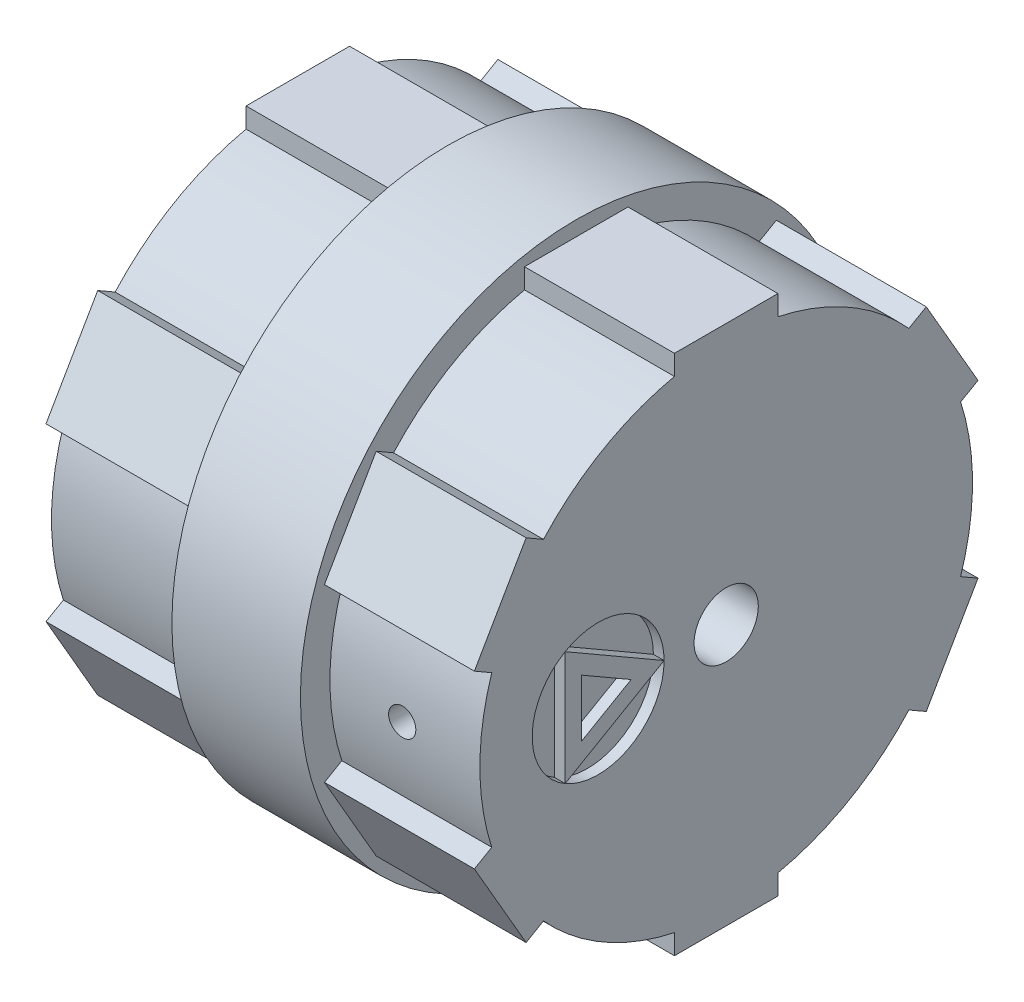
SolidWorks part; units mm, degrees
ref_plane "Front" through (0, 0, 0) normal (0, 0, 1) x (1, 0, 0)
ref_plane "Top" through (0, 0, 0) normal (0, 1, 0) x (1, 0, 0)
ref_plane "Right" through (0, 0, 0) normal (1, 0, 0) x (0, 0, -1)
sketch "Croquis1" plane through (0, 0, 0) normal (1, 0, 0) x (0, 0, -1)
  circle A0 centre (0, 0) radius 11.5
  dimension "D1" = 23
extrude "Saliente-Extruir1" add sketch "Croquis1" along normal blind 20
shell "Vaciado2" thickness 3
sketch "Croquis2" plane through (20, 0, 0) normal (1, 0, 0) x (0, 0, -1)
  circle A0 centre (0, 0) radius 1.5
extrude "Cortar-Extruir1" cut sketch "Croquis2" against normal blind 20
sketch "Croquis3" plane through (20, 0, 0) normal (1, 0, 0) x (0, 0, -1)
  line L0 (0, 13.2158) -> (0, -18.6677) construction
  line L1 (8.1622, 7.5015) -> (11.7564, 3.9985) construction
  line L2 (-2.4154, 10.8194) -> (2.4154, 10.8194)
  line L3 (-2.4154, 10.8194) -> (-2.4154, 12.1806)
  line L4 (-2.4154, 12.1806) -> (2.4154, 12.1806)
  line L5 (2.4154, 10.8194) -> (2.4154, 12.1806)
  line L6 (-2.4154, 10.8194) -> (2.4154, 12.1806) construction
  line L7 (-2.4154, 12.1806) -> (2.4154, 10.8194) construction
  line L8 (9.341, 8.1821) -> (10.5776, 3.3179) construction
  line L9 (8.1622, 7.5015) -> (9.341, 8.1821)
  line L10 (8.1622, 7.5015) -> (10.5776, 3.3179)
  line L11 (10.5776, 3.3179) -> (11.7564, 3.9985)
  line L12 (9.341, 8.1821) -> (11.7564, 3.9985)
  line L13 (10.5776, -3.3179) -> (9.341, -8.1821) construction
  line L14 (11.7564, -3.9985) -> (8.1622, -7.5015) construction
  line L15 (10.5776, -3.3179) -> (11.7564, -3.9985)
  line L16 (10.5776, -3.3179) -> (8.1622, -7.5015)
  line L17 (8.1622, -7.5015) -> (9.341, -8.1821)
  line L18 (11.7564, -3.9985) -> (9.341, -8.1821)
  line L19 (2.4154, -10.8194) -> (-2.4154, -12.1806) construction
  line L20 (2.4154, -12.1806) -> (-2.4154, -10.8194) construction
  line L21 (2.4154, -10.8194) -> (2.4154, -12.1806)
  line L22 (2.4154, -10.8194) -> (-2.4154, -10.8194)
  line L23 (-2.4154, -10.8194) -> (-2.4154, -12.1806)
  line L24 (2.4154, -12.1806) -> (-2.4154, -12.1806)
  line L25 (-8.1622, -7.5015) -> (-11.7564, -3.9985) construction
  line L26 (-9.341, -8.1821) -> (-10.5776, -3.3179) construction
  line L27 (-8.1622, -7.5015) -> (-9.341, -8.1821)
  line L28 (-8.1622, -7.5015) -> (-10.5776, -3.3179)
  line L29 (-10.5776, -3.3179) -> (-11.7564, -3.9985)
  line L30 (-9.341, -8.1821) -> (-11.7564, -3.9985)
  line L31 (-10.5776, 3.3179) -> (-9.341, 8.1821) construction
  line L32 (-11.7564, 3.9985) -> (-8.1622, 7.5015) construction
  line L33 (-10.5776, 3.3179) -> (-11.7564, 3.9985)
  line L34 (-10.5776, 3.3179) -> (-8.1622, 7.5015)
  line L35 (-8.1622, 7.5015) -> (-9.341, 8.1821)
  line L36 (-11.7564, 3.9985) -> (-9.341, 8.1821)
  circle A0 centre (0, 0) radius 11.5 construction
  point P3 (0, 11.5)
  point P13 (9.9593, 5.75)
  point P18 (9.9593, -5.75)
  point P23 (0, -11.5)
  point P28 (-9.9593, -5.75)
  point P33 (-9.9593, 5.75)
  point P38 (0, 0)
  dimension "D2" = 4.8308
  dimension "D3" = 1.3612
  dimension "D1" = 6
extrude "Saliente-Extruir2" add sketch "Croquis3" against normal through all
ref_plane "Plano1" through (0, 0, 0) normal (0, 0, 1) x (1, 0, 0)
sketch "Croquis4" plane through (0, 0, 0) normal (0, 0, 1) x (1, 0, 0)
  line L0 (20, 11.2435) -> (0, 11.2435) construction
  line L1 (7, 11.2435) -> (13, 11.2435)
  line L2 (7, 11.2435) -> (7, 12.8785)
  line L3 (7, 12.8785) -> (13, 12.8785)
  line L4 (13, 11.2435) -> (13, 12.8785)
  line L5 (0, 12.1806) -> (0, 11.2435) construction
  line L6 (20, 12.1806) -> (20, 11.2435) construction
  line L7 (-1.3796, 0) -> (22.7883, 0) construction
  dimension "D1" = 7
  dimension "D2" = 7
revolve "Revolución1" add sketch "Croquis4" angle 360 about L7
sketch "Croquis5" plane through (17, 0, 0) normal (-1, 0, 0) x (0, 0, 1)
  circle A0 centre (0, 0) radius 1.5
  circle A1 centre (0, 0) radius 4
  dimension "D1" = 8
  dimension "D2" = 3
extrude "Saliente-Extruir3" add sketch "Croquis5" along normal blind 4
sketch "Croquis6" plane through (20, 0, 0) normal (1, 0, 0) x (0, 0, -1)
  line L1 (-3.3528, 0) -> (-7.2903, 2.2733)
  line L2 (-7.2903, 2.2733) -> (-7.2903, -2.2733)
  line L3 (-7.2903, -2.2733) -> (-3.3528, 0)
  circle A0 centre (-5.9778, 0) radius 2.625
  circle A1 centre (-5.9778, 0) radius 1.3125 construction
  circle A2 centre (-5.9778, 0) radius 3.0795
  dimension "D1" = 5.25
extrude "Cortar-Extruir3" cut sketch "Croquis6" against normal blind 0.5 contours A2 A0 | L2 L3 L1
sketch "Croquis8" plane through (20, 0, 0) normal (1, 0, 0) x (0, 0, -1)
  line L1 (-2.8983, 0) -> (-7.5176, 2.667)
  line L2 (-7.5176, 2.667) -> (-7.5176, -2.667)
  line L3 (-7.5176, -2.667) -> (-2.8983, 0)
  line L4 (-4.438, 0) -> (-6.7477, 1.3335)
  line L5 (-6.7477, 1.3335) -> (-6.7477, -1.3335)
  line L6 (-6.7477, -1.3335) -> (-4.438, 0)
  circle A0 centre (-5.9778, 0) radius 1.5398 construction
  circle A1 centre (-5.9778, 0) radius 0.7699 construction
extrude "Saliente-Extruir4" add sketch "Croquis8" against normal blind 0.5 separate body
sketch "Croquis9" plane through (0, 0, 0) normal (0, 0, 1) x (1, 0, 0)
  circle A0 centre (16.3739, 0) radius 0.635
  dimension "D1" = 1.27
extrude "Cortar-Extruir4" cut sketch "Croquis9" along normal blind 20
